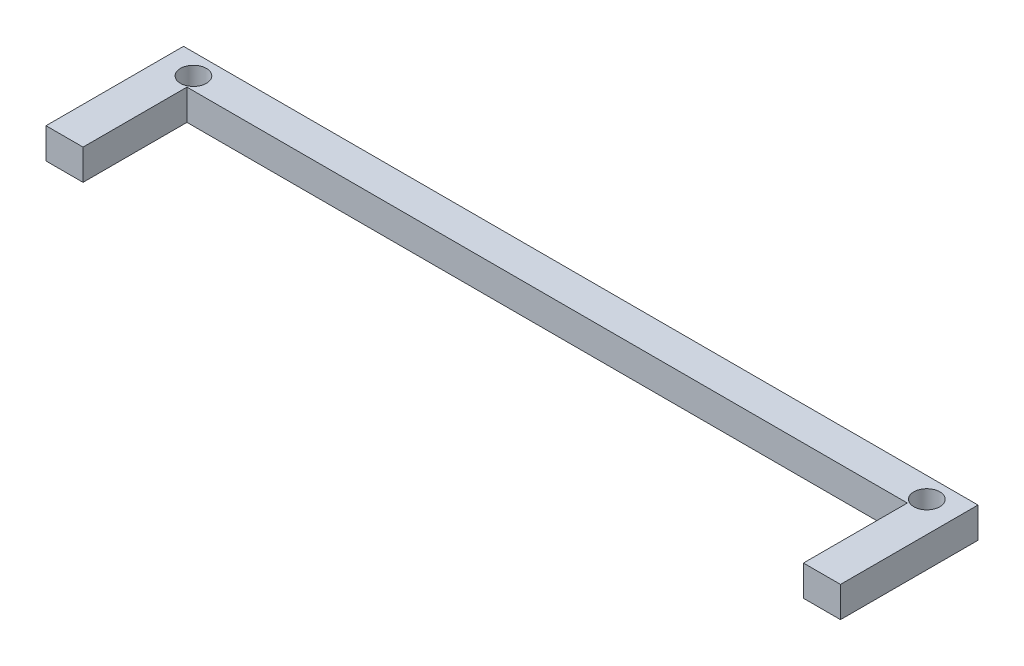
SolidWorks part; units mm, degrees
ref_plane "Front Plane" through (0, 0, 0) normal (0, 0, 1) x (1, 0, 0)
ref_plane "Top Plane" through (0, 0, 0) normal (0, 1, 0) x (1, 0, 0)
ref_plane "Right Plane" through (0, 0, 0) normal (1, 0, 0) x (0, 0, -1)
sketch "Sketch1" plane through (0, 0, 0) normal (0, 1, 0) x (1, 0, 0)
  line L0 (-55, 0) -> (55, 0) construction
  line L1 (-130, 11) -> (130, 11)
  line L3 (-117.875, 0) -> (117.875, 0)
  line L4 (130, 11) -> (130, 0)
  line L8 (-130, -34) -> (-117.875, -34)
  line L9 (-117.875, -34) -> (-117.875, 0)
  line L10 (0, -55) -> (0, 55) construction
  line L11 (130, -34) -> (117.875, -34)
  line L12 (117.875, -34) -> (117.875, 0)
  line L13 (130, 0) -> (130, -34)
  line L14 (-120, 4.25) -> (-120, 0) construction
  line L15 (-120, 4.25) -> (-130, 4.25) construction
  line L19 (-130, 11) -> (-130, -34)
  circle A0 centre (-120, 4.25) radius 4.25
  circle A1 centre (120, 4.25) radius 4.25
  point P2 (-123.9375, -34)
  point P6 (0, 0)
  dimension "D2" = 8.5
  dimension "D1" = 260
  dimension "D3" = 235.75
  dimension "D4" = 45
  dimension "D5" = 240
  dimension "D6" = 4.25
  dimension "D7" = 6.75
extrude "Boss-Extrude1" add sketch "Sketch1" along normal blind 10
